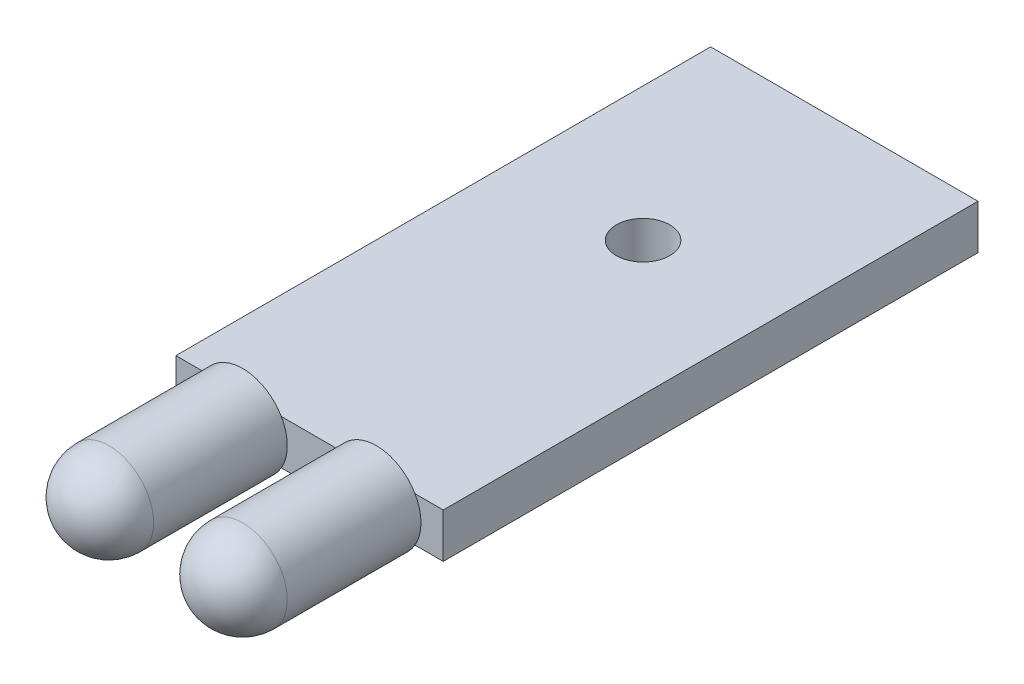
SolidWorks part; units mm, degrees
ref_plane "Front Plane" through (0, 0, 0) normal (0, 0, 1) x (1, 0, 0)
ref_plane "Top Plane" through (0, 0, 0) normal (0, 1, 0) x (1, 0, 0)
ref_plane "Right Plane" through (0, 0, 0) normal (1, 0, 0) x (0, 0, -1)
sketch "Sketch2" plane through (0, 0, 0) normal (0, 1, 0) x (1, 0, 0)
  line L1 (0, 0) -> (-15, 0)
  line L2 (0, 0) -> (0, 30)
  line L3 (0, 30) -> (-15, 30)
  line L4 (-15, 0) -> (-15, 30)
  dimension "D1" = 30
  dimension "D2" = 15
extrude "Boss-Extrude1" add sketch "Sketch2" along normal blind 2.5
sketch "Sketch3" plane through (0, 0, 0) normal (0, 0, 1) x (1, 0, 0)
  line L0 (-15, 1.25) -> (0, 1.25) construction
  line L1 (-15, 2.5) -> (-15, 0) construction
  line L2 (0, 2.5) -> (0, 0) construction
  line L3 (0, 1.25) -> (-7.5, 1.25) construction
  line L4 (-7.5, 1.25) -> (-15, 1.25)
  line L5 (-7.5, 2.5) -> (-7.5, 0) construction
  line L6 (-15, 2.5) -> (0, 2.5) construction
  line L7 (-15, 0) -> (0, 0) construction
  circle A0 centre (-11.25, 1.25) radius 2.5
  circle A1 centre (-3.75, 1.25) radius 2.5
  dimension "D1" = 5
extrude "Boss-Extrude2" add sketch "Sketch3" along normal blind 10 contours L4 A0 | L4 A0 | A1
fillet "Fillet3" radius 2.5 1 edges at (-8.75, 1.25, 10)
fillet "Fillet4" radius 2.5 1 edges at (-1.25, 1.25, 10)
sketch "Sketch4" plane through (0, 2.5, 0) normal (0, 1, 0) x (1, 0, 0)
  line L0 (-7.5, 30) -> (-7.5, 0) construction
  line L1 (0, 30) -> (-15, 30) construction
  line L2 (-9.0849, 0) -> (-5.9151, 0) construction
  point P6 (-7.5, 18.71)
  dimension "D1" = 11.29
hole_wizard "Ø3.0mm Dowel Hole1" positions "Sketch4" profile "Sketch5" hole size "Ø3.0" standard "ANSI Metric"
sketch "Sketch5" plane through (-7.5, 2.5, -18.71) normal (1, 0, 0) x (0, 0, 1)
  line L0 (0, 0) -> (0, 12.9013)
  line L1 (0, 12.9013) -> (1.5, 12)
  line L2 (1.5, 12) -> (1.5, 0)
  line L5 (1.5, 0) -> (0, 0)
  line L10 (0, 12.9013) -> (-1.5, 12) construction
  line L11 (0, -6.35) -> (0, 107.95) construction
  dimension "Hole Dia." = 3
  dimension "Hole Depth" = 12
  dimension "Drill Angle" = 118
